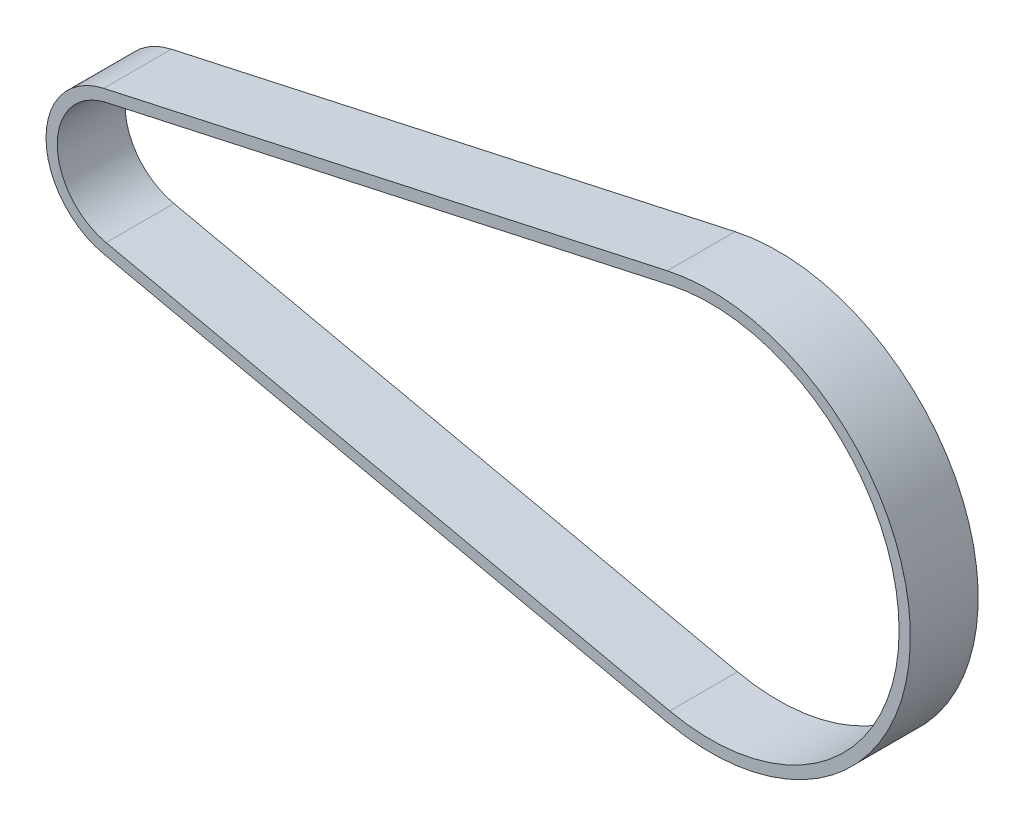
SolidWorks part; units mm, degrees
material "HYPALON"
ref_plane "Alzado" through (0, 0, 0) normal (0, 0, 1) x (1, 0, 0)
ref_plane "Planta" through (0, 0, 0) normal (0, 1, 0) x (1, 0, 0)
ref_plane "Vista lateral" through (0, 0, 0) normal (1, 0, 0) x (0, 0, -1)
sketch "Croquis1" plane through (0, 0, 0) normal (0, 0, 1) x (1, 0, 0)
  line L0 (-1.1799, 5.3719) -> (48.713, 16.3307)
  line L1 (-1.1799, -5.3719) -> (48.713, -16.3307)
  line L2 (-1.3945, 6.3487) -> (48.4985, 17.3074)
  line L3 (-1.3945, -6.3487) -> (48.4985, -17.3074)
  arc A0 (-1.1799, 5.3719) -> (-1.1799, -5.3719) centre (0, 0) ccw
  arc A1 (48.713, -16.3307) -> (48.713, 16.3307) centre (52.3, 0) ccw
  arc A2 (48.4985, -17.3074) -> (48.4985, 17.3074) centre (52.3, 0) ccw
  arc A3 (-1.3945, 6.3487) -> (-1.3945, -6.3487) centre (0, 0) ccw
  dimension "D1" = 11
  dimension "D2" = 33.44
  dimension "D3" = 52.3
  dimension "D4" = 1
extrude "Saliente-Extruir1" add sketch "Croquis1" along normal blind 6
